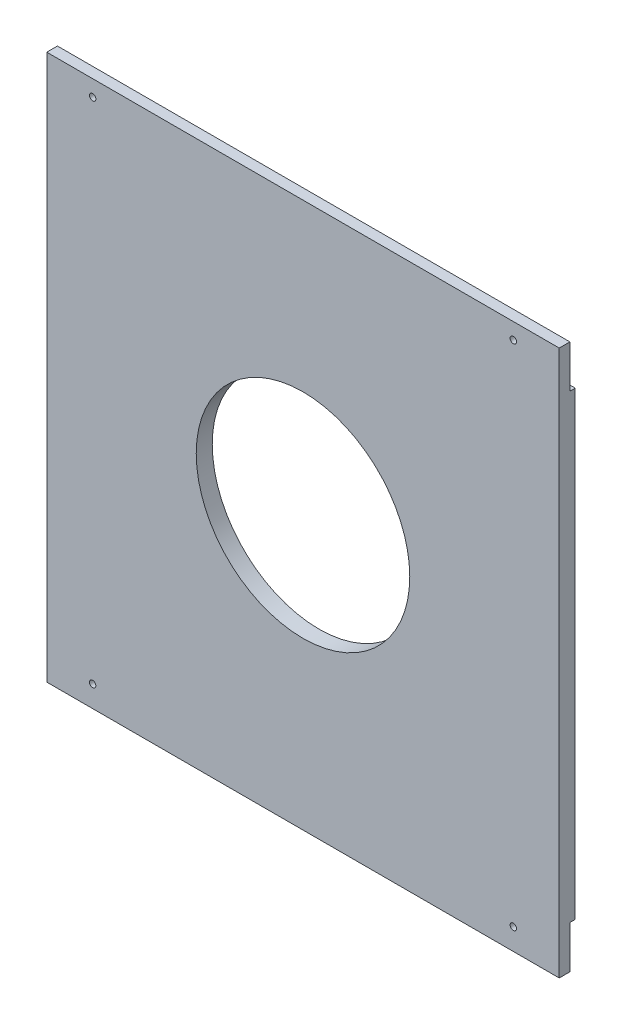
SolidWorks part; units mm, degrees
ref_plane "Front Plane" through (0, 0, 0) normal (0, 0, 1) x (1, 0, 0)
ref_plane "Top Plane" through (0, 0, 0) normal (0, 1, 0) x (1, 0, 0)
ref_plane "Right Plane" through (0, 0, 0) normal (1, 0, 0) x (0, 0, -1)
sketch "Sketch1" plane through (0, 0, 0) normal (0, 0, 1) x (1, 0, 0)
  line L0 (-285.7122, 240.5) -> (290.0853, 240.5) construction
  line L1 (-240, 255.5) -> (240, 255.5)
  line L2 (-240, 255.5) -> (-240, -255.5)
  line L3 (-240, -255.5) -> (240, -255.5)
  line L4 (240, 255.5) -> (240, -255.5)
  line L5 (-197, 283.5256) -> (-197, -327.2571) construction
  line L6 (-377.5483, -235.5) -> (335.2745, -235.5) construction
  line L7 (0, 621.1568) -> (0, -564.1033) construction
  circle A0 centre (-197, 240.5) radius 3
  circle A1 centre (-197, -235.5) radius 3
  circle A2 centre (197, -235.5) radius 3
  circle A3 centre (197, 240.5) radius 3
  dimension "D8" = 6
  dimension "D9" = 6
  dimension "D1" = 480
  dimension "D2" = 511
  dimension "D3" = 255.5
  dimension "D4" = 240
  dimension "D5" = 15
  dimension "D6" = 43
  dimension "D7" = 20
extrude "Boss-Extrude1" add sketch "Sketch1" along normal blind 15
sketch "Sketch2" plane through (0, 0, 0) normal (0, 0, -1) x (-1, 0, 0)
  line L0 (240, 255.5) -> (240, -255.5) construction
  line L1 (-240, 255.5) -> (240, 255.5)
  line L2 (-240, 255.5) -> (-240, 215.5)
  line L3 (-240, 215.5) -> (240, 215.5)
  line L4 (240, 255.5) -> (240, 215.5)
  line L6 (240, 255.5) -> (200, 255.5)
  line L7 (240, 255.5) -> (240, -255.5)
  line L8 (-240, 255.5) -> (-200, 255.5)
  line L9 (240, -255.5) -> (200, -255.5)
  line L10 (-240, -255.5) -> (240, -255.5)
  line L11 (-240, -255.5) -> (-240, -215.5)
  line L12 (-240, -215.5) -> (240, -215.5)
  line L13 (240, -255.5) -> (240, -215.5)
  line L14 (200, 255.5) -> (200, -255.5)
  line M1 (240, -255.5) -> (240, 255.5)
  line M2 (240, 255.5) -> (-240, 255.5)
  line M3 (-240, 255.5) -> (-240, -255.5)
  line M4 (-240, -255.5) -> (240, -255.5)
  circle M5 centre (197, 240.5) radius 3
  circle M6 centre (197, -235.5) radius 3
  circle M7 centre (-197, -235.5) radius 3
  circle M8 centre (-197, 240.5) radius 3
  dimension "D1" = 40
  dimension "D2" = 40
  dimension "D3" = 40
  dimension "D4" = 40
extrude "Cut-Extrude1" cut sketch "Sketch2" against normal blind 5 contours L14 L1 L3 M2 M3 M5 M8 | L14 L3 M2 M1 | L3 L14 L12 L7 | L12 L14 M4 M1 | L14 L12 M3 M4 M6 M7
sketch "Sketch3" plane through (0, 0, 0) normal (0, 0, -1) x (-1, 0, 0)
  circle A0 centre (0, 0) radius 100
  dimension "D1" = 200
extrude "Cut-Extrude2" cut sketch "Sketch3" against normal blind 15
sketch "Sketch4" plane through (0, 0, 0) normal (0, 0, -1) x (-1, 0, 0)
  line L0 (0, 0) -> (0, 296.6386) construction
  line L1 (0, 0) -> (203.6664, -117.5868) construction
  line L2 (0, 0) -> (-388.0138, -224.0199) construction
  line L3 (0, 0) -> (370.2851, 213.7842) construction
  line L4 (0, 0) -> (-391.4743, 226.0178) construction
  line L5 (0, 0) -> (0, -384.5891) construction
  line L6 (0, 0) -> (39.2781, 298.347) construction
  circle A0 centre (0, 0) radius 174.75 construction
  circle A1 centre (22.8095, 173.255) radius 1.5
  circle A2 centre (-22.8095, 173.255) radius 1.5
  circle A3 centre (-161.4479, -66.8739) radius 1.5
  circle A4 centre (-138.6385, -106.3811) radius 1.5
  circle A5 centre (138.6385, -106.3811) radius 1.5
  circle A6 centre (161.4479, -66.8739) radius 1.5
  dimension "D6" = 349.5
  dimension "D1" = 120
  dimension "D2" = 120
  dimension "D3" = 60
  dimension "D4" = 60
  dimension "D5" = 60
  dimension "D7" = 7.5
extrude "Cut-Extrude3" cut sketch "Sketch4" against normal blind 7
sketch "Sketch5" plane through (0, 0, 0) normal (0, 0, -1) x (-1, 0, 0)
  line L0 (0, 0) -> (0, 311.9546) construction
  line L1 (22.8095, 176.4304) -> (20.0595, 174.8427)
  line L2 (20.0595, 174.8427) -> (20.0595, 171.6673)
  line L3 (20.0595, 171.6673) -> (22.8095, 170.0796)
  line L4 (22.8095, 170.0796) -> (25.5595, 171.6673)
  line L5 (25.5595, 171.6673) -> (25.5595, 174.8427)
  line L6 (25.5595, 174.8427) -> (22.8095, 176.4304)
  line L7 (-20.0595, 174.8427) -> (-20.0595, 171.6673)
  line L8 (-20.0595, 171.6673) -> (-22.8095, 170.0796)
  line L9 (-22.8095, 170.0796) -> (-25.5595, 171.6673)
  line L10 (-25.5595, 171.6673) -> (-25.5595, 174.8427)
  line L11 (-25.5595, 174.8427) -> (-22.8095, 176.4304)
  line L12 (-22.8095, 176.4304) -> (-20.0595, 174.8427)
  line L13 (0, 0) -> (-333.48, 192.5348) construction
  line L14 (-164.1979, -68.4616) -> (-161.4479, -70.0494)
  line L15 (-164.1979, -65.2862) -> (-164.1979, -68.4616)
  line L16 (-161.4479, -63.6985) -> (-164.1979, -65.2862)
  line L17 (-158.6979, -65.2862) -> (-161.4479, -63.6985)
  line L18 (-158.6979, -68.4616) -> (-158.6979, -65.2862)
  line L19 (-161.4479, -70.0494) -> (-158.6979, -68.4616)
  line L20 (-138.6385, -109.5565) -> (-141.3885, -107.9688)
  line L21 (-135.8885, -107.9688) -> (-138.6385, -109.5565)
  line L22 (-135.8885, -104.7933) -> (-135.8885, -107.9688)
  line L23 (-138.6385, -103.2056) -> (-135.8885, -104.7933)
  line L24 (-141.3885, -104.7933) -> (-138.6385, -103.2056)
  line L25 (-141.3885, -107.9688) -> (-141.3885, -104.7933)
  line L26 (0, 0) -> (285.7658, 164.9869) construction
  line L27 (141.3885, -107.9688) -> (141.3885, -104.7933)
  line L28 (138.6385, -109.5565) -> (141.3885, -107.9688)
  line L29 (135.8885, -107.9688) -> (138.6385, -109.5565)
  line L30 (135.8885, -104.7933) -> (135.8885, -107.9688)
  line L31 (138.6385, -103.2056) -> (135.8885, -104.7933)
  line L32 (141.3885, -104.7933) -> (138.6385, -103.2056)
  line L33 (164.1979, -65.2862) -> (164.1979, -68.4616)
  line L34 (161.4479, -63.6985) -> (164.1979, -65.2862)
  line L35 (158.6979, -65.2862) -> (161.4479, -63.6985)
  line L36 (158.6979, -68.4616) -> (158.6979, -65.2862)
  line L37 (161.4479, -70.0494) -> (158.6979, -68.4616)
  line L38 (164.1979, -68.4616) -> (161.4479, -70.0494)
  circle A0 centre (22.8095, 173.255) radius 2.75 construction
  circle A1 centre (-138.6385, -106.3811) radius 2.75 construction
  circle A2 centre (161.4479, -66.8739) radius 2.75 construction
  dimension "D1" = 60
  dimension "D2" = 60
extrude "Cut-Extrude4" cut sketch "Sketch5" against normal blind 2.3
sketch "Sketch6" plane through (0, 0, 0) normal (0, 0, -1) x (-1, 0, 0)
  circle A0 centre (-156.9115, 135.0103) radius 40 construction
  circle A1 centre (0, 0) radius 165 construction
  circle A2 centre (-156.9115, 135.0103) radius 3
  dimension "D1" = 330
  dimension "D2" = 80
  dimension "D3" = 207
extrude "Cut-Extrude5" cut sketch "Sketch6" against normal blind 7
sketch "Sketch7" plane through (0, 0, 0) normal (0, 0, -1) x (-1, 0, 0)
  line L0 (-156.9115, 135.0103) -> (-156.9115, 182.5103) construction
  line L1 (-156.9115, 135.0103) -> (-110.4062, 181.5156) construction
  line L2 (-156.9115, 135.0103) -> (-210.5598, 188.6585) construction
  line L3 (-156.9115, 135.0103) -> (-190.4991, 101.4227) construction
  circle A0 centre (-156.9115, 135.0103) radius 47.5 construction
  circle A1 centre (-123.324, 168.5978) radius 1.5
  circle A2 centre (-190.4991, 168.5978) radius 1.5
  circle A3 centre (-190.4991, 101.4227) radius 1.5
  dimension "D1" = 95
  dimension "D5" = 3
  dimension "D6" = 3
  dimension "D7" = 3
  dimension "D2" = 45
  dimension "D3" = 45
  dimension "D4" = 90
extrude "Cut-Extrude6" cut sketch "Sketch7" against normal blind 5
